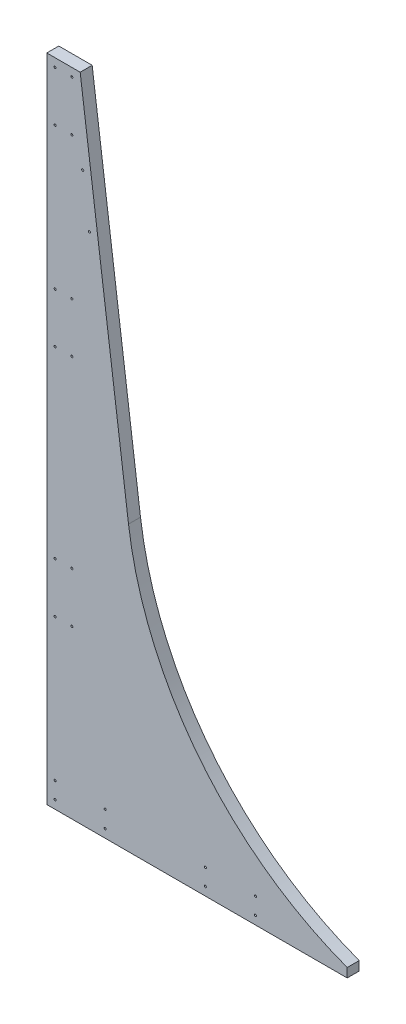
SolidWorks part; units mm, degrees
material "Pine"
ref_plane "Front Plane" through (0, 0, 0) normal (0, 0, 1) x (1, 0, 0)
ref_plane "Top Plane" through (0, 0, 0) normal (0, 1, 0) x (1, 0, 0)
ref_plane "Right Plane" through (0, 0, 0) normal (1, 0, 0) x (0, 0, -1)
sketch "Sketch1" plane through (0, 0, 0) normal (0, 0, 1) x (1, 0, 0)
  line L0 (0, 0) -> (500, 0)
  line L1 (0, 0) -> (0, 990.6)
  line L3 (0, 990.6) -> (50.8, 990.6)
  line L4 (50.8, 990.6) -> (124.3674, 431.8)
  line L7 (457.201, 13.862) -> (457.201, 0)
  arc A9 (124.3674, 431.8) -> (500, 0) centre (638.1166, 499.4364) ccw
  dimension "D18" = 50.8
  dimension "D1" = 500
  dimension "D2" = 990.6
  dimension "D3" = 42.799
  dimension "D4" = 50.8
  dimension "D5" = 558.8
  dimension "D6" = 97.5
extrude "Boss-Extrude1" add sketch "Sketch1" along normal blind 18.2562
sketch "Sketch2" plane through (0, 0, 18.2562) normal (0, 0, 1) x (1, 0, 0)
  line L0 (0, 990.6) -> (50.8, 990.6) construction
  line L1 (0, 0) -> (0, 990.6) construction
  line L2 (12.7, 977.9) -> (38.1, 977.9) construction
  line L3 (38.1, 977.9) -> (38.1, 901.7) construction
  line L4 (38.1, 901.7) -> (12.7, 901.7) construction
  line L5 (12.7, 901.7) -> (12.7, 977.9) construction
  line L6 (12.7, 901.7) -> (12.7, 685.8) construction
  line L7 (12.7, 609.6) -> (38.1, 609.6) construction
  line L8 (12.7, 685.8) -> (12.7, 609.6) construction
  line L9 (38.1, 685.8) -> (12.7, 685.8) construction
  line L10 (12.7, 254) -> (12.7, 38.1) construction
  line L11 (12.7, 254) -> (12.7, 330.2) construction
  line L12 (12.7, 330.2) -> (38.1, 330.2) construction
  line L13 (38.1, 330.2) -> (38.1, 254) construction
  line L14 (38.1, 254) -> (12.7, 254) construction
  line L15 (12.7, 38.1) -> (88.9, 38.1) construction
  line L16 (88.9, 38.1) -> (88.9, 12.7) construction
  line L17 (88.9, 12.7) -> (12.7, 12.7) construction
  line L18 (12.7, 12.7) -> (12.7, 38.1) construction
  line L20 (88.9, 38.1) -> (241.3, 38.1) construction
  line L21 (241.3, 38.1) -> (317.5, 38.1) construction
  line L22 (317.5, 38.1) -> (317.5, 12.7) construction
  line L23 (317.5, 12.7) -> (241.3, 12.7) construction
  line L24 (241.3, 12.7) -> (241.3, 38.1) construction
  circle A0 centre (12.7, 977.9) radius 1.5875
  circle A1 centre (38.1, 977.9) radius 1.5875
  circle A2 centre (12.7, 901.7) radius 1.5875
  circle A3 centre (38.1, 901.7) radius 1.5875
  circle A4 centre (12.7, 609.6) radius 1.5875
  circle A5 centre (38.1, 609.6) radius 1.5875
  circle A6 centre (12.7, 685.8) radius 1.5875
  circle A7 centre (38.1, 685.8) radius 1.5875
  circle A8 centre (12.7, 254) radius 1.5875
  circle A9 centre (38.1, 254) radius 1.5875
  circle A10 centre (12.7, 330.2) radius 1.5875
  circle A11 centre (38.1, 330.2) radius 1.5875
  circle A12 centre (12.7, 38.1) radius 1.5875
  circle A13 centre (12.7, 12.7) radius 1.5875
  circle A14 centre (88.9, 38.1) radius 1.5875
  circle A15 centre (88.9, 12.7) radius 1.5875
  circle A16 centre (241.3, 38.1) radius 1.5875
  circle A17 centre (317.5, 38.1) radius 1.5875
  circle A18 centre (241.3, 12.7) radius 1.5875
  circle A19 centre (317.5, 12.7) radius 1.5875
  dimension "D1" = 3.175
  dimension "D3" = 25.4
  dimension "D4" = 12.7
  dimension "D10" = 279.4
  dimension "D13" = 215.9
  dimension "D2" = 12.7
  dimension "D5" = 76.2
  dimension "D6" = 215.9
  dimension "D7" = 76.2
  dimension "D8" = 25.4
  dimension "D9" = 25.4
  dimension "D11" = 76.2
  dimension "D12" = 25.4
  dimension "D14" = 25.4
  dimension "D15" = 76.2
  dimension "D16" = 25.4
  dimension "D17" = 76.2
  dimension "D18" = 152.4
extrude "Cut-Extrude1" cut sketch "Sketch2" against normal through all
sketch "Sketch3" plane through (0, 0, 18.2562) normal (0, 0, 1) x (1, 0, 0)
  line L0 (64.7422, 787.4) -> (54.7103, 863.6) construction
  line L1 (50.8, 990.6) -> (124.3674, 431.8) construction
  line L3 (0, 990.6) -> (50.8, 990.6) construction
  circle A0 centre (64.7422, 787.4) radius 1.5875
  circle A1 centre (54.7103, 863.6) radius 1.5875
  dimension "D1" = 3.175
  dimension "D2" = 12.7
  dimension "D3" = 127
  dimension "D4" = 76.2
extrude "Cut-Extrude2" cut sketch "Sketch3" against normal through all
